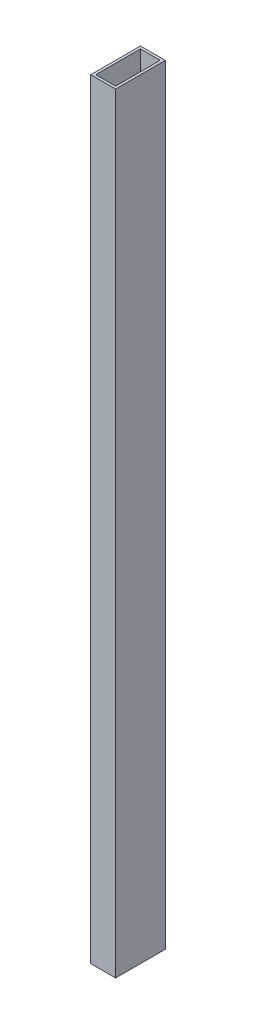
SolidWorks part; units mm, degrees
ref_plane "Спереди" through (0, 0, 0) normal (0, 0, 1) x (1, 0, 0)
ref_plane "Сверху" through (0, 0, 0) normal (0, 1, 0) x (1, 0, 0)
ref_plane "Справа" through (0, 0, 0) normal (1, 0, 0) x (0, 0, -1)
sketch "Эскиз1" plane through (0, 0, 0) normal (0, 1, 0) x (1, 0, 0)
  line L1 (-38.5882, 31.8869) -> (-18.5882, 31.8869)
  line L2 (-38.5882, 31.8869) -> (-38.5882, -8.1131)
  line L3 (-38.5882, -8.1131) -> (-18.5882, -8.1131)
  line L4 (-18.5882, 31.8869) -> (-18.5882, -8.1131)
  line L5 (-36.5882, 29.8869) -> (-20.5882, 29.8869)
  line L6 (-36.5882, 29.8869) -> (-36.5882, -6.1131)
  line L7 (-36.5882, -6.1131) -> (-20.5882, -6.1131)
  line L8 (-20.5882, 29.8869) -> (-20.5882, -6.1131)
  dimension "D1" = 20
  dimension "D2" = 40
  dimension "D3" = 2
  dimension "D4" = 2
  dimension "D5" = 2
  dimension "D6" = 2
extrude "Бобышка-Вытянуть1" add sketch "Эскиз1" along normal blind 620
